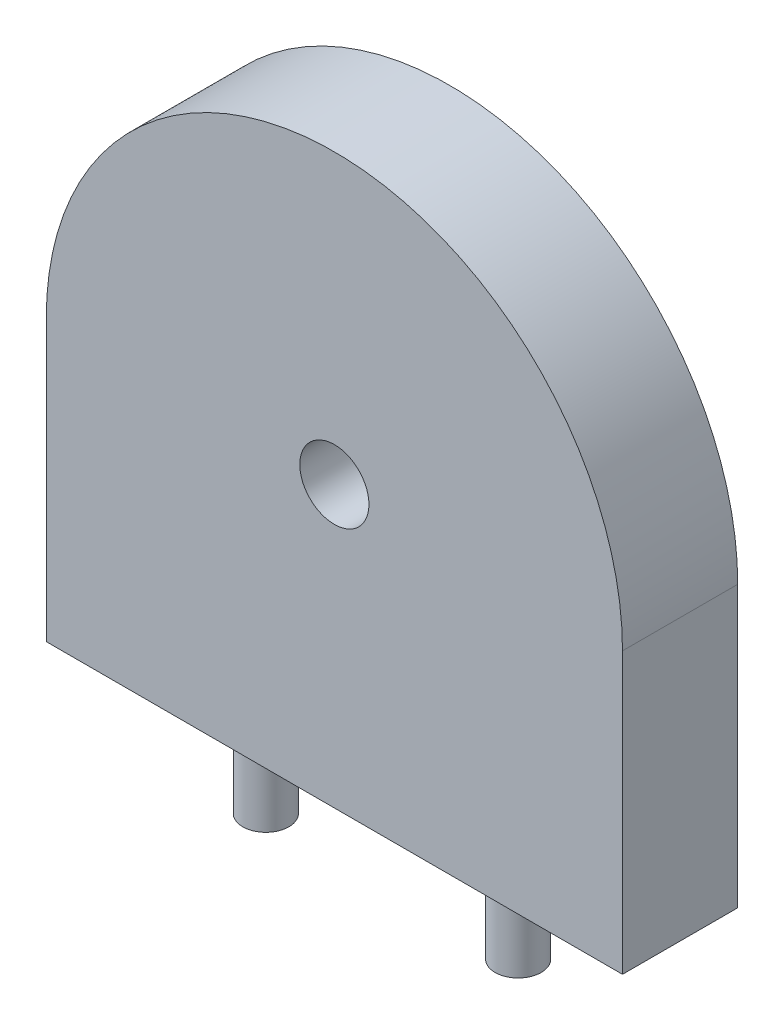
SolidWorks part; units mm, degrees
ref_plane "Plan de face" through (0, 0, 0) normal (0, 0, 1) x (1, 0, 0)
ref_plane "Plan de dessus" through (0, 0, 0) normal (0, 1, 0) x (1, 0, 0)
ref_plane "Plan de droite" through (0, 0, 0) normal (1, 0, 0) x (0, 0, -1)
sketch "Esquisse1" plane through (0, 0, 0) normal (0, 0, 1) x (1, 0, 0)
  line L1 (-25, -12.35) -> (25, -12.35)
  line L2 (-25, -12.35) -> (-25, 12.35)
  line L4 (25, -12.35) -> (25, 12.35)
  circle A0 centre (0, 12.35) radius 3
  arc A1 (-25, 12.35) -> (25, 12.35) centre (0, 12.35) cw
  point P0 (0, 0)
extrude "Boss.-Extru.1" add sketch "Esquisse1" along normal blind 10
sketch "Esquisse2" plane through (0, -12.35, 0) normal (0, -1, 0) x (1, 0, 0)
  circle A0 centre (-10.946, 5) radius 2
  circle A1 centre (10.946, 5) radius 2
extrude "Boss.-Extru.2" add sketch "Esquisse2" along normal blind 8
sketch "Esquisse6" plane through (0, 0, 10) normal (0, 0, 1) x (1, 0, 0)
  line L0 (-25, -12.35) -> (-25, -12.77)
  line L1 (25, -12.35) -> (-25, -12.35)
  line L2 (25, -12.35) -> (25, -12.77)
  line L3 (25, -12.77) -> (-25, -12.77)
  point P7 (0, 0)
extrude "Boss.-Extru.4" add sketch "Esquisse6" against normal up to surface (10 mm away) up to face at (0, 6.25, 0)
sketch "Esquisse7" plane through (0, 0, 10) normal (0, 0, 1) x (1, 0, 0)
  line L0 (-25, -12.77) -> (-25, -11.96)
  line L1 (-25, 12.35) -> (-25, -12.77) construction
  line L2 (-25, -11.96) -> (25, -11.96)
  line L3 (25, -12.77) -> (25, 12.35) construction
  line L4 (25, -11.96) -> (25, -12.77)
  line L5 (25, -12.77) -> (-25, -12.77)
extrude "Enlèv. mat.-Extru.3" cut sketch "Esquisse7" against normal blind 10
sketch "Esquisse8" plane through (0, -11.96, 0) normal (0, -1, 0) x (1, 0, 0)
  circle A0 centre (-10.946, 5) radius 2
  circle A1 centre (10.946, 5) radius 2
extrude "Boss.-Extru.5" add sketch "Esquisse8" along normal up to surface (8.39 mm away) up to face at (-10.946, -20.35, 3)
